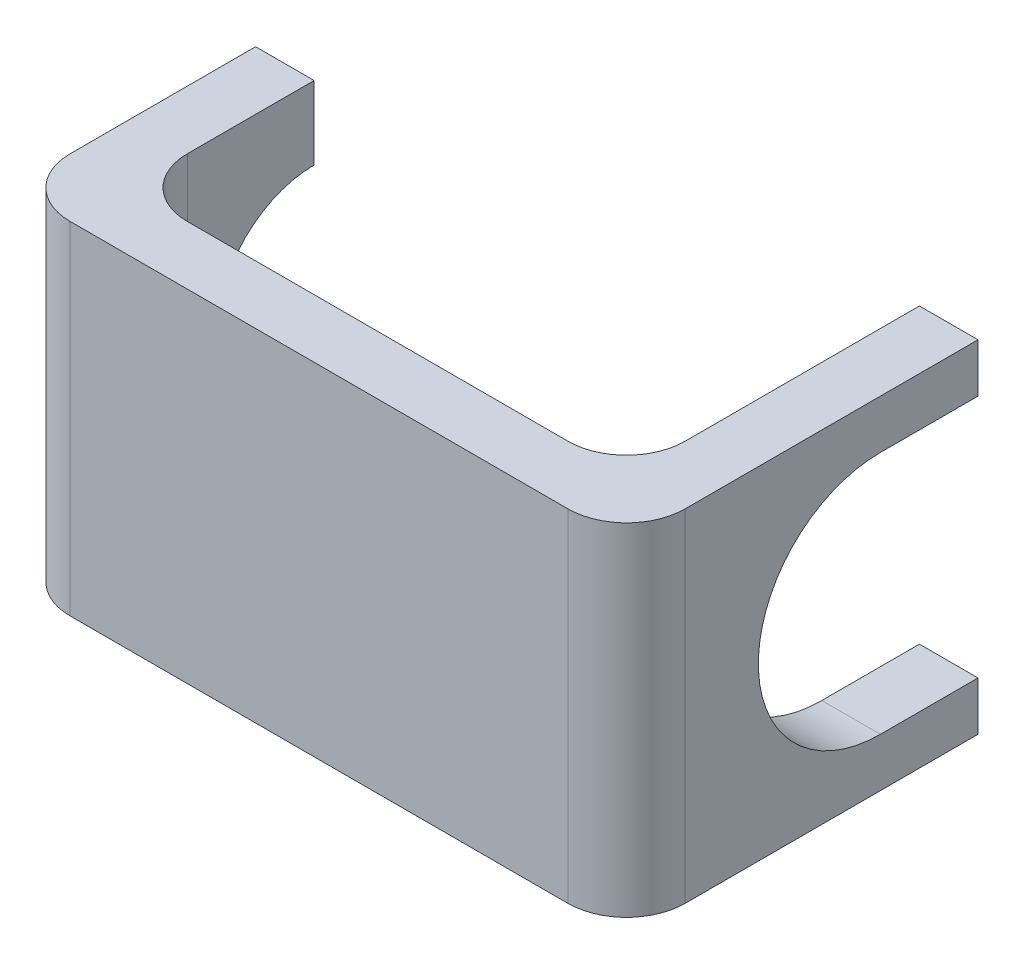
SolidWorks part; units mm, degrees
ref_plane "Front Plane" through (0, 0, 0) normal (0, 0, 1) x (1, 0, 0)
ref_plane "Top Plane" through (0, 0, 0) normal (0, 1, 0) x (1, 0, 0)
ref_plane "Right Plane" through (0, 0, 0) normal (1, 0, 0) x (0, 0, -1)
sketch "Sketch1" plane through (0, 0, 0) normal (0, 1, 0) x (1, 0, 0)
  line L0 (0, 0) -> (0, 1.9)
  line L1 (0, 1.9) -> (-0.6, 1.9)
  line L2 (-0.6, 1.9) -> (-0.6, -0.6)
  line L3 (-0.6, -0.6) -> (5.7, -0.6)
  line L4 (0, 0) -> (5.1, 0)
  line L5 (5.1, 0) -> (5.1, 3)
  line L6 (5.1, 3) -> (5.7, 3)
  line L7 (5.7, 3) -> (5.7, -0.6)
  dimension "D3" = 0.6
  dimension "D4" = 0.6
  dimension "D5" = 0.6
  dimension "D1" = 3.6
  dimension "D6" = 2.5
  dimension "D2" = 6.3
extrude "Boss-Extrude1" add sketch "Sketch1" along normal blind 3.5
fillet "Fillet1" radius 0.6 4 edges at (5.7, 1.75, 0.6) (5.1, 1.75, 0) (-0.6, 1.75, 0.6) (0, 1.75, 0)
sketch "Sketch2" plane through (5.7, 0, 0) normal (1, 0, 0) x (0, 0, -1)
  line L0 (2, 3) -> (3, 3)
  line L1 (3, 0.5) -> (2, 0.5)
  line L2 (3, 3.5) -> (3, 0) construction
  line L3 (3, 3.5) -> (3, 0) construction
  line L4 (3, 0.5) -> (3, 3)
  circle A0 centre (2, 1.75) radius 1.25 construction
  arc A1 (2, 3) -> (2, 0.5) centre (2, 1.75) ccw
  point P10 (3, 1.75)
  point P11 (3, 1.75)
  dimension "D1" = 2.5
  dimension "D2" = 1
extrude "Cut-Extrude1" cut sketch "Sketch2" against normal blind 4
sketch "Sketch3" plane through (-0.6, 0, 0) normal (-1, 0, 0) x (0, 0, 1)
  line L0 (-1.9, 3.5) -> (-1.9, 0) construction
  line L1 (-1.9, 0.75) -> (-1.9, 2.75)
  arc A0 (-1.9, 2.75) -> (-1.9, 0.75) centre (-1.9, 1.75) cw
  point P5 (0, 0)
  point P6 (-1.9, 1.9802)
  point P7 (-1.9, 1.75)
  dimension "D1" = 2
extrude "Cut-Extrude2" cut sketch "Sketch3" against normal blind 10
equation "\"D4@Sketch1\"=\"D3@Sketch1\""
equation "\"D5@Sketch1\"=\"D3@Sketch1\""
